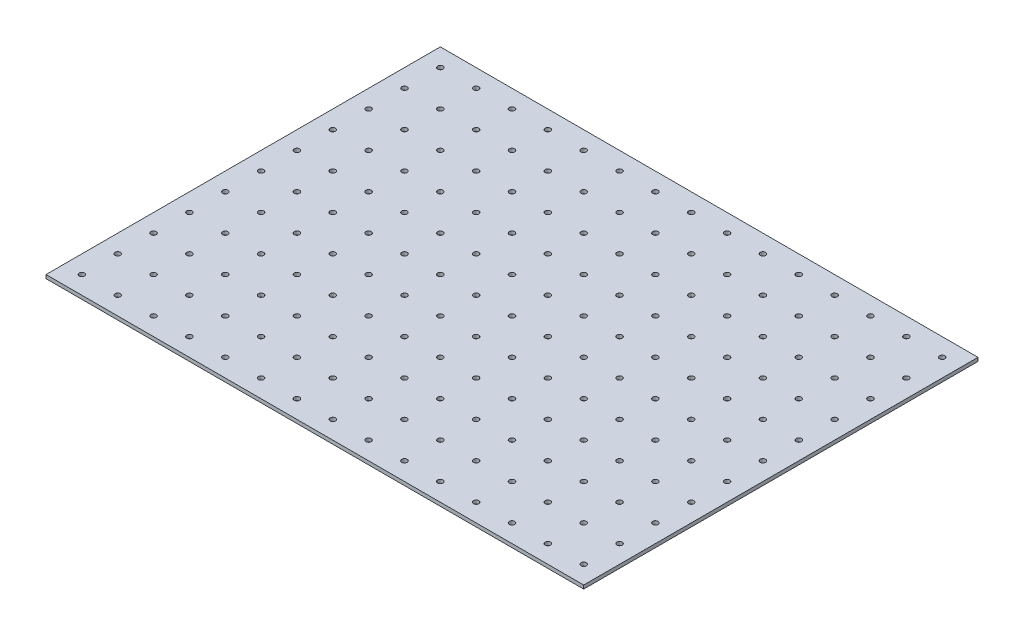
SolidWorks part; units mm, degrees
ref_plane "Front Plane" through (0, 0, 0) normal (0, 0, 1) x (1, 0, 0)
ref_plane "Top Plane" through (0, 0, 0) normal (0, 1, 0) x (1, 0, 0)
ref_plane "Right Plane" through (0, 0, 0) normal (1, 0, 0) x (0, 0, -1)
sketch "Sketch1" plane through (0, 0, 0) normal (0, 1, 0) x (1, 0, 0)
  line L1 (-150, 110) -> (150, 110)
  line L2 (-150, 110) -> (-150, -110)
  line L3 (-150, -110) -> (150, -110)
  line L4 (150, 110) -> (150, -110)
  line L5 (-150, 110) -> (150, -110) construction
  line L6 (-150, -110) -> (150, 110) construction
  point P0 (0, 0)
  dimension "D1" = 300
  dimension "D2" = 220
extrude "Boss-Extrude1" add sketch "Sketch1" along normal mid plane 2
sketch "Sketch3" plane through (0, 1, 0) normal (0, 1, 0) x (1, 0, 0)
  line L0 (150, 110) -> (-150, 110) construction
  line L1 (-150, 110) -> (-150, -110) construction
  circle A0 centre (-140, 100) radius 1.5
  circle A1 centre (-120, 100) radius 1.5
  circle A2 centre (-100, 100) radius 1.5
  circle A3 centre (-80, 100) radius 1.5
  circle A4 centre (-60, 100) radius 1.5
  circle A5 centre (-40, 100) radius 1.5
  circle A6 centre (-20, 100) radius 1.5
  circle A7 centre (0, 100) radius 1.5
  circle A8 centre (20, 100) radius 1.5
  circle A9 centre (40, 100) radius 1.5
  circle A10 centre (60, 100) radius 1.5
  circle A11 centre (80, 100) radius 1.5
  circle A12 centre (100, 100) radius 1.5
  circle A13 centre (120, 100) radius 1.5
  circle A14 centre (140, 100) radius 1.5
  circle A15 centre (-120, 80) radius 1.5
  circle A16 centre (-100, 80) radius 1.5
  circle A17 centre (-80, 80) radius 1.5
  circle A18 centre (-60, 80) radius 1.5
  circle A19 centre (-40, 80) radius 1.5
  circle A20 centre (-20, 80) radius 1.5
  circle A21 centre (0, 80) radius 1.5
  circle A22 centre (20, 80) radius 1.5
  circle A23 centre (40, 80) radius 1.5
  circle A24 centre (60, 80) radius 1.5
  circle A25 centre (80, 80) radius 1.5
  circle A26 centre (100, 80) radius 1.5
  circle A27 centre (120, 80) radius 1.5
  circle A28 centre (140, 80) radius 1.5
  circle A29 centre (-120, 60) radius 1.5
  circle A30 centre (-100, 60) radius 1.5
  circle A31 centre (-80, 60) radius 1.5
  circle A32 centre (-60, 60) radius 1.5
  circle A33 centre (-40, 60) radius 1.5
  circle A34 centre (-20, 60) radius 1.5
  circle A35 centre (0, 60) radius 1.5
  circle A36 centre (20, 60) radius 1.5
  circle A37 centre (40, 60) radius 1.5
  circle A38 centre (60, 60) radius 1.5
  circle A39 centre (80, 60) radius 1.5
  circle A40 centre (100, 60) radius 1.5
  circle A41 centre (120, 60) radius 1.5
  circle A42 centre (140, 60) radius 1.5
  circle A43 centre (-120, 40) radius 1.5
  circle A44 centre (-100, 40) radius 1.5
  circle A45 centre (-80, 40) radius 1.5
  circle A46 centre (-60, 40) radius 1.5
  circle A47 centre (-40, 40) radius 1.5
  circle A48 centre (-20, 40) radius 1.5
  circle A49 centre (0, 40) radius 1.5
  circle A50 centre (20, 40) radius 1.5
  circle A51 centre (40, 40) radius 1.5
  circle A52 centre (60, 40) radius 1.5
  circle A53 centre (80, 40) radius 1.5
  circle A54 centre (100, 40) radius 1.5
  circle A55 centre (120, 40) radius 1.5
  circle A56 centre (140, 40) radius 1.5
  circle A57 centre (-120, 20) radius 1.5
  circle A58 centre (-100, 20) radius 1.5
  circle A59 centre (-80, 20) radius 1.5
  circle A60 centre (-60, 20) radius 1.5
  circle A61 centre (-40, 20) radius 1.5
  circle A62 centre (-20, 20) radius 1.5
  circle A63 centre (0, 20) radius 1.5
  circle A64 centre (20, 20) radius 1.5
  circle A65 centre (40, 20) radius 1.5
  circle A66 centre (60, 20) radius 1.5
  circle A67 centre (80, 20) radius 1.5
  circle A68 centre (100, 20) radius 1.5
  circle A69 centre (120, 20) radius 1.5
  circle A70 centre (140, 20) radius 1.5
  circle A71 centre (-120, 0) radius 1.5
  circle A72 centre (-100, 0) radius 1.5
  circle A73 centre (-80, 0) radius 1.5
  circle A74 centre (-60, 0) radius 1.5
  circle A75 centre (-40, 0) radius 1.5
  circle A76 centre (-20, 0) radius 1.5
  circle A77 centre (0, 0) radius 1.5
  circle A78 centre (20, 0) radius 1.5
  circle A79 centre (40, 0) radius 1.5
  circle A80 centre (60, 0) radius 1.5
  circle A81 centre (80, 0) radius 1.5
  circle A82 centre (100, 0) radius 1.5
  circle A83 centre (120, 0) radius 1.5
  circle A84 centre (140, 0) radius 1.5
  circle A85 centre (-120, -20) radius 1.5
  circle A86 centre (-100, -20) radius 1.5
  circle A87 centre (-80, -20) radius 1.5
  circle A88 centre (-60, -20) radius 1.5
  circle A89 centre (-40, -20) radius 1.5
  circle A90 centre (-20, -20) radius 1.5
  circle A91 centre (0, -20) radius 1.5
  circle A92 centre (20, -20) radius 1.5
  circle A93 centre (40, -20) radius 1.5
  circle A94 centre (60, -20) radius 1.5
  circle A95 centre (80, -20) radius 1.5
  circle A96 centre (100, -20) radius 1.5
  circle A97 centre (120, -20) radius 1.5
  circle A98 centre (140, -20) radius 1.5
  circle A99 centre (-120, -40) radius 1.5
  circle A100 centre (-100, -40) radius 1.5
  circle A101 centre (-80, -40) radius 1.5
  circle A102 centre (-60, -40) radius 1.5
  circle A103 centre (-40, -40) radius 1.5
  circle A104 centre (-20, -40) radius 1.5
  circle A105 centre (0, -40) radius 1.5
  circle A106 centre (20, -40) radius 1.5
  circle A107 centre (40, -40) radius 1.5
  circle A108 centre (60, -40) radius 1.5
  circle A109 centre (80, -40) radius 1.5
  circle A110 centre (100, -40) radius 1.5
  circle A111 centre (120, -40) radius 1.5
  circle A112 centre (140, -40) radius 1.5
  circle A113 centre (-120, -60) radius 1.5
  circle A114 centre (-100, -60) radius 1.5
  circle A115 centre (-80, -60) radius 1.5
  circle A116 centre (-60, -60) radius 1.5
  circle A117 centre (-40, -60) radius 1.5
  circle A118 centre (-20, -60) radius 1.5
  circle A119 centre (0, -60) radius 1.5
  circle A120 centre (20, -60) radius 1.5
  circle A121 centre (40, -60) radius 1.5
  circle A122 centre (60, -60) radius 1.5
  circle A123 centre (80, -60) radius 1.5
  circle A124 centre (100, -60) radius 1.5
  circle A125 centre (120, -60) radius 1.5
  circle A126 centre (140, -60) radius 1.5
  circle A127 centre (-120, -80) radius 1.5
  circle A128 centre (-100, -80) radius 1.5
  circle A129 centre (-80, -80) radius 1.5
  circle A130 centre (-60, -80) radius 1.5
  circle A131 centre (-40, -80) radius 1.5
  circle A132 centre (-20, -80) radius 1.5
  circle A133 centre (0, -80) radius 1.5
  circle A134 centre (20, -80) radius 1.5
  circle A135 centre (40, -80) radius 1.5
  circle A136 centre (60, -80) radius 1.5
  circle A137 centre (80, -80) radius 1.5
  circle A138 centre (100, -80) radius 1.5
  circle A139 centre (120, -80) radius 1.5
  circle A140 centre (140, -80) radius 1.5
  circle A141 centre (-120, -100) radius 1.5
  circle A142 centre (-100, -100) radius 1.5
  circle A143 centre (-80, -100) radius 1.5
  circle A144 centre (-60, -100) radius 1.5
  circle A145 centre (-40, -100) radius 1.5
  circle A146 centre (-20, -100) radius 1.5
  circle A147 centre (0, -100) radius 1.5
  circle A148 centre (20, -100) radius 1.5
  circle A149 centre (40, -100) radius 1.5
  circle A150 centre (60, -100) radius 1.5
  circle A151 centre (80, -100) radius 1.5
  circle A152 centre (100, -100) radius 1.5
  circle A153 centre (120, -100) radius 1.5
  circle A154 centre (140, -100) radius 1.5
  circle A155 centre (-140, 80) radius 1.5
  circle A156 centre (-140, 60) radius 1.5
  circle A157 centre (-140, 40) radius 1.5
  circle A158 centre (-140, 20) radius 1.5
  circle A159 centre (-140, 0) radius 1.5
  circle A160 centre (-140, -20) radius 1.5
  circle A161 centre (-140, -40) radius 1.5
  circle A162 centre (-140, -60) radius 1.5
  circle A163 centre (-140, -80) radius 1.5
  circle A164 centre (-140, -100) radius 1.5
  dimension "D1" = 3
  dimension "D2" = 10
  dimension "D3" = 10
  dimension "D4" = 15
  dimension "D5" = 11
extrude "Cut-Extrude1" cut sketch "Sketch3" against normal through all
